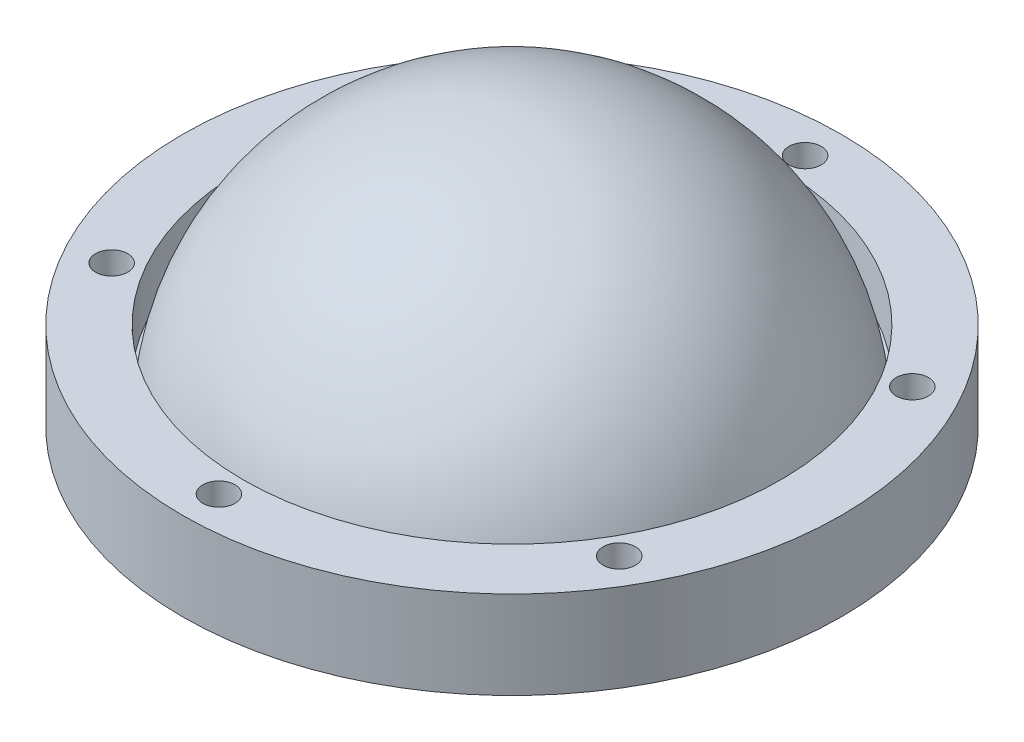
SolidWorks part; units mm, degrees
ref_plane "Front" through (0, 0, 0) normal (0, 0, 1) x (1, 0, 0)
ref_plane "Top" through (0, 0, 0) normal (0, 1, 0) x (1, 0, 0)
ref_plane "Right" through (0, 0, 0) normal (1, 0, 0) x (0, 0, -1)
sketch "Sketch1" plane through (0, 0, 0) normal (0, 0, 1) x (1, 0, 0)
  line L2 (-65, 0) -> (-65, 5)
  line L3 (-65, 5) -> (-54.7723, 5)
  line L8 (0, 0) -> (0, 55) construction
  line L9 (0, 55) -> (0, 50)
  line L10 (-65, 0) -> (55, 0) construction
  line L11 (-65, 0) -> (-50, 0)
  arc A0 (55, 0) -> (-55, 0) centre (0, 0) ccw construction
  arc A1 (0, 50) -> (-50, 0) centre (0, 0) ccw
  arc A2 (-54.7723, 5) -> (0, 55) centre (0, 0) cw
  dimension "D1" = 110
  dimension "D2" = 100
  dimension "D3" = 10
  dimension "D6" = 5
revolve "Revolve1" add sketch "Sketch1" angle 360 about L8
sketch "Sketch2" plane through (0, 0, 0) normal (0, 1, 0) x (1, 0, 0)
  circle A0 centre (0, 0) radius 67.5
  dimension "D1" = 135
  dimension "D2" = 0
extrude "Boss-Extrude1" add sketch "Sketch2" along normal blind 8
sketch "Sketch4" plane through (0, 0, 0) normal (0, -1, 0) x (-1, 0, 0)
  line L1 (0, 67.5) -> (0, 52.5) construction
  circle A0 centre (0, 0) radius 67.5 construction
  circle A1 centre (0, 52.5) radius 3.3
  dimension "D2" = 6.6
  dimension "D1" = 15
sketch "Sketch6" plane through (0, 8, 0) normal (0, 1, 0) x (1, 0, 0)
  circle A0 centre (0, 0) radius 55
  circle A1 centre (0, 0) radius 67.5
  dimension "D1" = 110
  dimension "D2" = 135
extrude "Boss-Extrude2" add sketch "Sketch6" along normal blind 10 contours A1 | A0
sketch "Sketch7" plane through (0, 18, 0) normal (0, 1, 0) x (1, 0, 0)
  line L0 (0, 0) -> (0, -60) construction
  circle A0 centre (0, -60) radius 3.3
  dimension "D1" = 6.6
  dimension "D2" = 60
extrude "Cut-Extrude3" cut sketch "Sketch7" against normal blind 15 contours A0
pattern_circular "CirPattern2" count 6 over 360 about axis through (0, 0, 0) along (0, 1, 0) of "Cut-Extrude3"
